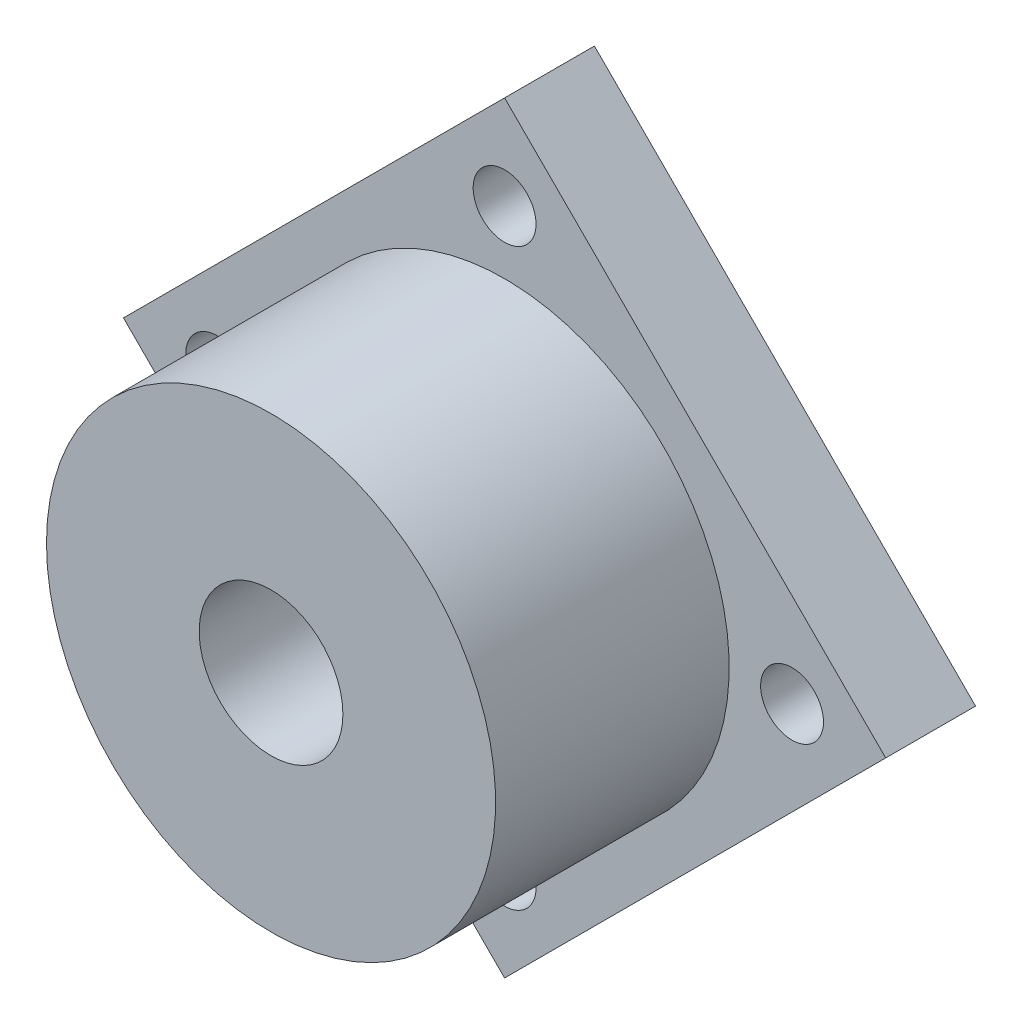
SolidWorks part; units mm, degrees
ref_plane "前视基准面" through (0, 0, 0) normal (0, 0, 1) x (1, 0, 0)
ref_plane "上视基准面" through (0, 0, 0) normal (0, 1, 0) x (1, 0, 0)
ref_plane "右视基准面" through (0, 0, 0) normal (1, 0, 0) x (0, 0, -1)
other "Configuration Table"
sketch "草图1" plane through (0, 0, 0) normal (0, 0, 1) x (1, 0, 0)
  line L1 (0, 21.2132) -> (-21.2132, 0)
  line L2 (-21.2132, 0) -> (0, -21.2132)
  line L3 (0, -21.2132) -> (21.2132, 0)
  line L4 (21.2132, 0) -> (0, 21.2132)
  circle A0 centre (0, 0) radius 15 construction
  circle A1 centre (0, 0) radius 4
  dimension "D2" = 8
  dimension "D1" = 30
extrude "凸台-拉伸1" add sketch "草图1" along normal blind 5
sketch "草图2" plane through (0, 0, 5) normal (0, 0, 1) x (1, 0, 0)
  circle A0 centre (16, 0) radius 1.75
  circle A1 centre (0, 0) radius 16 construction
  circle A2 centre (0, -16) radius 1.75
  circle A3 centre (0, 0) radius 16 construction
  circle A4 centre (-16, 0) radius 1.75
  circle A5 centre (0, 0) radius 16 construction
  circle A6 centre (0, 16) radius 1.75
  circle A7 centre (0, 0) radius 16 construction
  point P17 (0, 0)
  dimension "D1" = 32
  dimension "D3" = 3.5
  dimension "D2" = 4
extrude "切除-拉伸1" cut sketch "草图2" against normal blind 5
sketch "草图3" plane through (0, 0, 5) normal (0, 0, 1) x (1, 0, 0)
  circle A0 centre (0, 0) radius 4 construction
  circle A1 centre (0, 0) radius 4
  circle A2 centre (0, 0) radius 12.5
  dimension "D1" = 25
extrude "凸台-拉伸2" add sketch "草图3" along normal blind 13
